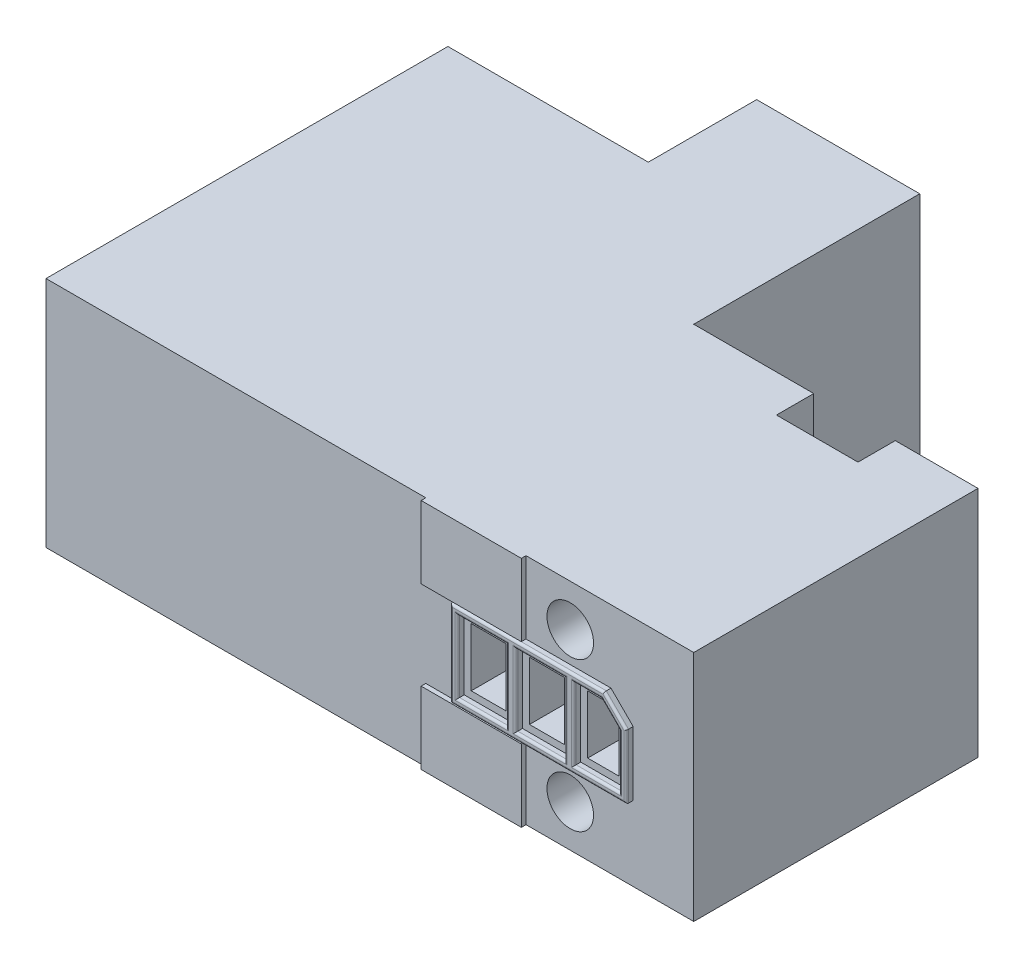
SolidWorks part; units mm, degrees
ref_plane "Front Plane" through (0, 0, 0) normal (0, 0, 1) x (1, 0, 0)
ref_plane "Top Plane" through (0, 0, 0) normal (0, 1, 0) x (1, 0, 0)
ref_plane "Right Plane" through (0, 0, 0) normal (1, 0, 0) x (0, 0, -1)
sketch "Sketch1" plane through (0, 0, 0) normal (0, 1, 0) x (1, 0, 0)
  line L0 (0, 0) -> (27.8, 0)
  line L1 (27.8, 0) -> (27.8, 12.2)
  line L2 (27.8, 12.2) -> (15.6, 12.2)
  line L3 (15.6, 12.2) -> (15.6, 21.9)
  line L4 (15.6, 21.9) -> (8.6, 21.9)
  line L5 (8.6, 21.9) -> (8.6, 17.25)
  line L6 (8.6, 17.25) -> (0, 17.25)
  line L7 (0, 17.25) -> (0, 0)
  dimension "D1" = 27.8
  dimension "D2" = 12.2
  dimension "D3" = 17.25
  dimension "D4" = 4.65
  dimension "D5" = 12.2
  dimension "D6" = 8.6
extrude "Boss-Extrude1" add sketch "Sketch1" along normal blind 10
sketch "Sketch2" plane through (0, 0, 0) normal (0, 0, 1) x (1, 0, 0)
  line L0 (0, 0) -> (27.8, 0) construction
  line L1 (18.25, 6.3) -> (19.75, 6.3)
  line L2 (18.25, 6.3) -> (18.25, 3.8)
  line L3 (18.25, 3.8) -> (19.75, 3.8)
  line L4 (19.75, 6.3) -> (19.75, 3.8)
  line L5 (20.75, 6.3) -> (22.25, 6.3)
  line L6 (20.75, 6.3) -> (20.75, 3.8)
  line L7 (20.75, 3.8) -> (22.25, 3.8)
  line L8 (22.25, 6.3) -> (22.25, 3.8)
  line L9 (23.25, 6.3) -> (24, 6.3)
  line L10 (23.25, 6.3) -> (23.25, 3.8)
  line L11 (23.25, 3.8) -> (24.6, 3.8)
  line L12 (24.6, 3.8) -> (24.6, 5.7)
  line L13 (24.6, 5.7) -> (24, 6.3)
  line L14 (27.8, 10) -> (27.8, 0) construction
  dimension "D1" = 2.5
  dimension "D2" = 1.5
  dimension "D3" = 1.5
  dimension "D4" = 2.5
  dimension "D5" = 1
  dimension "D6" = 1.35
  dimension "D7" = 2.5
  dimension "D8" = 1
  dimension "D9" = 3.8
  dimension "D10" = 3.8
  dimension "D11" = 3.8
  dimension "D12" = 3.2
extrude "Cut-Extrude1" cut sketch "Sketch2" against normal blind 17.9
sketch "Sketch3" plane through (0, 0, 0) normal (0, 0, 1) x (1, 0, 0)
  line L1 (27.8, 10) -> (27.8, 0) construction
  line L2 (0, 10) -> (27.8, 10) construction
  line L3 (27.8, 5) -> (25.9391, 5) construction
  circle A0 centre (22.5, 8.2) radius 1
  circle A1 centre (22.5, 1.8) radius 1
  dimension "D1" = 2
  dimension "D2" = 5.3
  dimension "D3" = 1.8
extrude "Cut-Extrude2" cut sketch "Sketch3" against normal through all
sketch "Sketch4" plane through (0, 0, -12.2) normal (0, 0, -1) x (-1, 0, 0)
  line L0 (-24.25, 8.2) -> (-24.25, 11.1651)
  line L1 (-24.25, 11.1651) -> (-20.75, 11.1651)
  line L2 (-20.75, 11.1651) -> (-20.75, 8.2)
  line L3 (-27.4208, 5) -> (-25.9391, 5) construction
  line L4 (-20.75, -1.1651) -> (-20.75, 1.8)
  line L5 (-24.25, -1.1651) -> (-20.75, -1.1651)
  line L6 (-24.25, 1.8) -> (-24.25, -1.1651)
  arc A0 (-24.25, 8.2) -> (-20.75, 8.2) centre (-22.5, 8.2) ccw
  arc A1 (-24.25, 1.8) -> (-20.75, 1.8) centre (-22.5, 1.8) cw
extrude "Cut-Extrude3" cut sketch "Sketch4" against normal blind 1.6
sketch "Sketch5" plane through (0, 0, 0) normal (0, 0, 1) x (1, 0, 0)
  line L17 (17.95, 6.6) -> (20.05, 6.6)
  line L18 (20.05, 6.6) -> (20.05, 3.5)
  line L19 (17.95, 3.5) -> (20.05, 3.5)
  line L20 (17.95, 6.6) -> (17.95, 3.5)
  line L21 (20.45, 6.6) -> (22.55, 6.6)
  line L22 (22.55, 6.6) -> (22.55, 3.5)
  line L23 (20.45, 3.5) -> (22.55, 3.5)
  line L24 (20.45, 6.6) -> (20.45, 3.5)
  line L25 (22.95, 6.6) -> (24.1243, 6.6)
  line L26 (24.9, 5.8243) -> (24.1243, 6.6)
  line L27 (24.9, 3.5) -> (24.9, 5.8243)
  line L28 (22.95, 3.5) -> (24.9, 3.5)
  line L29 (22.95, 6.6) -> (22.95, 3.5)
  line L30 (17.65, 6.9) -> (17.65, 3.2)
  line L31 (17.65, 3.2) -> (20.35, 3.2)
  line L33 (17.65, 6.9) -> (24.2485, 6.9)
  line L34 (25.2, 5.9485) -> (24.2485, 6.9)
  line L37 (20.35, 3.2) -> (25.2, 3.2)
  line L38 (25.2, 3.2) -> (25.2, 5.9485)
extrude "Boss-Extrude2" add sketch "Sketch5" along normal blind 0.3
fillet "Fillet1" radius 0.1 18 edges at (24.9, 4.6621, 0.3) (24.5121, 6.2121, 0.3) (23.5371, 6.6, 0.3) (22.95, 5.05, 0.3) (23.925, 3.5, 0.3) (20.05, 5.05, 0.3) (19, 6.6, 0.3) (17.95, 5.05, 0.3) (19, 3.5, 0.3) (24.7243, 6.4243, 0.3) (25.2, 4.5743, 0.3) (21.425, 3.2, 0.3) (17.65, 5.05, 0.3) (20.9493, 6.9, 0.3) (22.55, 5.05, 0.3) (21.5, 6.6, 0.3) (20.45, 5.05, 0.3) (21.5, 3.5, 0.3)
sketch "Sketch6" plane through (0, 0, 0) normal (0, 0, 1) x (1, 0, 0)
  line L0 (0, 10) -> (27.8, 10) construction
  line L1 (16.3, 10) -> (20.6, 10)
  line L2 (16.3, 10) -> (16.3, 6.9)
  line L3 (16.3, 6.9) -> (20.6, 6.9)
  line L4 (20.6, 10) -> (20.6, 6.9)
  line L5 (24.2485, 6.9) -> (17.65, 6.9) construction
  line L6 (27.8, 10) -> (27.8, 0) construction
  line L7 (27.8, 5) -> (26.3473, 5) construction
  line L8 (20.6, 0) -> (20.6, 3.1)
  line L9 (16.3, 3.1) -> (20.6, 3.1)
  line L10 (16.3, 0) -> (16.3, 3.1)
  line L11 (16.3, 0) -> (20.6, 0)
  dimension "D1" = 4.3
  dimension "D2" = 7.2
extrude "Boss-Extrude3" add sketch "Sketch6" along normal blind 0.2
